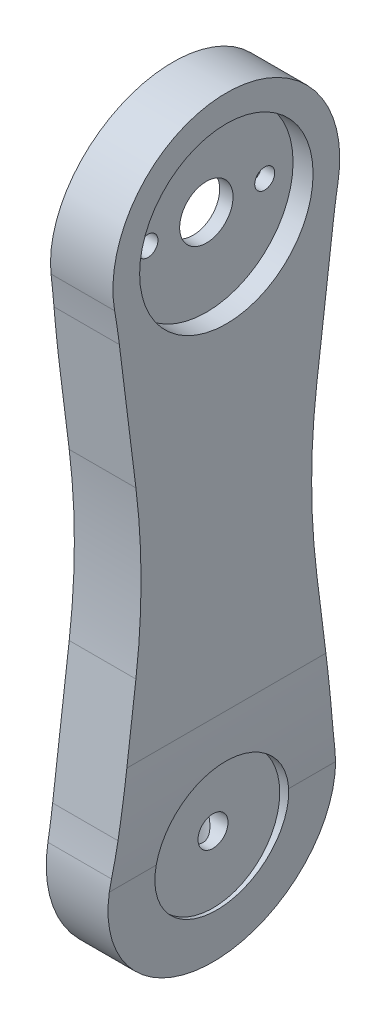
SolidWorks part; units mm, degrees
ref_plane "Alzado" through (0, 0, 0) normal (0, 0, 1) x (1, 0, 0)
ref_plane "Planta" through (0, 0, 0) normal (0, 1, 0) x (1, 0, 0)
ref_plane "Vista lateral" through (0, 0, 0) normal (1, 0, 0) x (0, 0, -1)
sketch "Croquis1" plane through (0, 0, 0) normal (1, 0, 0) x (0, 0, -1)
  line L0 (-16.0394, 7.6583) -> (-13.5578, 27.5108)
  line L2 (16.0394, 7.6583) -> (13.5578, 27.5108)
  line L4 (-12.7856, 39.9143) -> (12.7856, 39.9143)
  arc A0 (-16.7482, 2.915) -> (16.7482, 2.915) centre (0, 0) ccw
  arc A6 (16.7482, 2.915) -> (16.0394, 7.6583) centre (115.2672, 20.0618) cw
  arc A7 (-16.7482, 2.915) -> (-16.0394, 7.6583) centre (-115.2672, 20.0618) ccw
  arc A8 (13.5578, 27.5108) -> (12.7856, 39.9143) centre (112.7856, 39.9143) cw
  arc A9 (-13.5578, 27.5108) -> (-12.7856, 39.9143) centre (-112.7856, 39.9143) ccw
  point P21 (0, -17)
  dimension "D1" = 17
  dimension "D2" = 100
extrude "Saliente-Extruir1" add sketch "Croquis1" against normal blind 10
sketch "Croquis3" plane through (0, 0, 0) normal (1, 0, 0) x (0, 0, -1)
  circle A0 centre (0, 0) radius 10
  dimension "D1" = 20
extrude "Cortar-Extruir1" cut sketch "Croquis3" against normal blind 2
sketch "Croquis7" plane through (-2, 0, 0) normal (1, 0, 0) x (0, 0, -1)
  circle A0 centre (0, 0) radius 2.25
  dimension "D1" = 4.5
extrude "Cortar-Extruir5" cut sketch "Croquis7" against normal blind 10 and the other way through all
sketch "Croquis8" plane through (0, 0, 0) normal (0, 1, 0) x (1, 0, 0)
  line L0 (-10, 17) -> (-10, -17) construction
  circle A0 centre (-6, 0) radius 2.5
  dimension "D2" = 5
  dimension "D1" = 4
extrude "Cortar-Extruir6" cut sketch "Croquis8" against normal blind 19
sketch "Croquis12" plane through (0, 0, 0) normal (0, 1, 0) x (1, 0, 0)
  circle A0 centre (-6, 0) radius 3.5
  dimension "D1" = 7
extrude "Cortar-Extruir19" cut sketch "Croquis12" against normal blind 5 from offset 11 offset against normal yes
mirror "Simetría1" about plane through (-10, 39.9143, 12.7856) normal (0, 1, 0) of "Saliente-Extruir1", "Cortar-Extruir1", "Cortar-Extruir5"
sketch "Croquis13" plane through (-2, 0, 0) normal (1, 0, 0) x (0, 0, -1)
  circle A0 centre (0, 79.8285) radius 4
  circle A1 centre (8.75, 79.8285) radius 1.5
  circle A2 centre (-8.75, 79.8285) radius 1.5
  dimension "D1" = 8
  dimension "D4" = 3
  dimension "D2" = 17.5
  dimension "D3" = 8.75
extrude "Cortar-Extruir20" cut sketch "Croquis13" against normal through all both and the other way through all
sketch "Croquis15" plane through (0, 0, 0) normal (1, 0, 0) x (0, 0, -1)
  circle A0 centre (0, 79.8285) radius 13
  dimension "D1" = 26
sketch "Croquis17" plane through (-10, 0, 0) normal (-1, 0, 0) x (0, 0, 1)
  circle A0 centre (0, 79.8285) radius 13
extrude "Cortar-Extruir22" cut sketch "Croquis17" against normal blind 5
extrude "Cortar-Extruir23" cut sketch "Croquis15" against normal blind 3
sketch "Croquis18" plane through (0, 0, 0) normal (0, 0, 1) x (1, 0, 0)
  line L0 (-8, 96.8285) -> (0, 96.8285)
  line L5 (-2, -17) -> (-10, -17)
  line L6 (-10, -17) -> (-10, 63.2018)
  line L7 (-9.4074, 78.5865) -> (-8, 96.8285)
  line L8 (0, 96.8285) -> (0, 16.6267)
  line L9 (-0.5926, 1.2421) -> (-2, -17)
  arc A0 (0, 16.6267) -> (-0.5926, 1.2421) centre (-200, 16.6267) cw
  arc A1 (-10, 63.2018) -> (-9.4074, 78.5865) centre (190, 63.2018) cw
  point P4 (0, 8.923)
  point P9 (-10, 70.9056)
  dimension "D5" = 200
  dimension "D1" = 8
  dimension "D2" = 26
  dimension "D3" = 87.9056
  dimension "D4" = 87.9056
extrude "Cortar-Extruir24" cut sketch "Croquis18" against normal through all both and the other way through all flip side to cut
